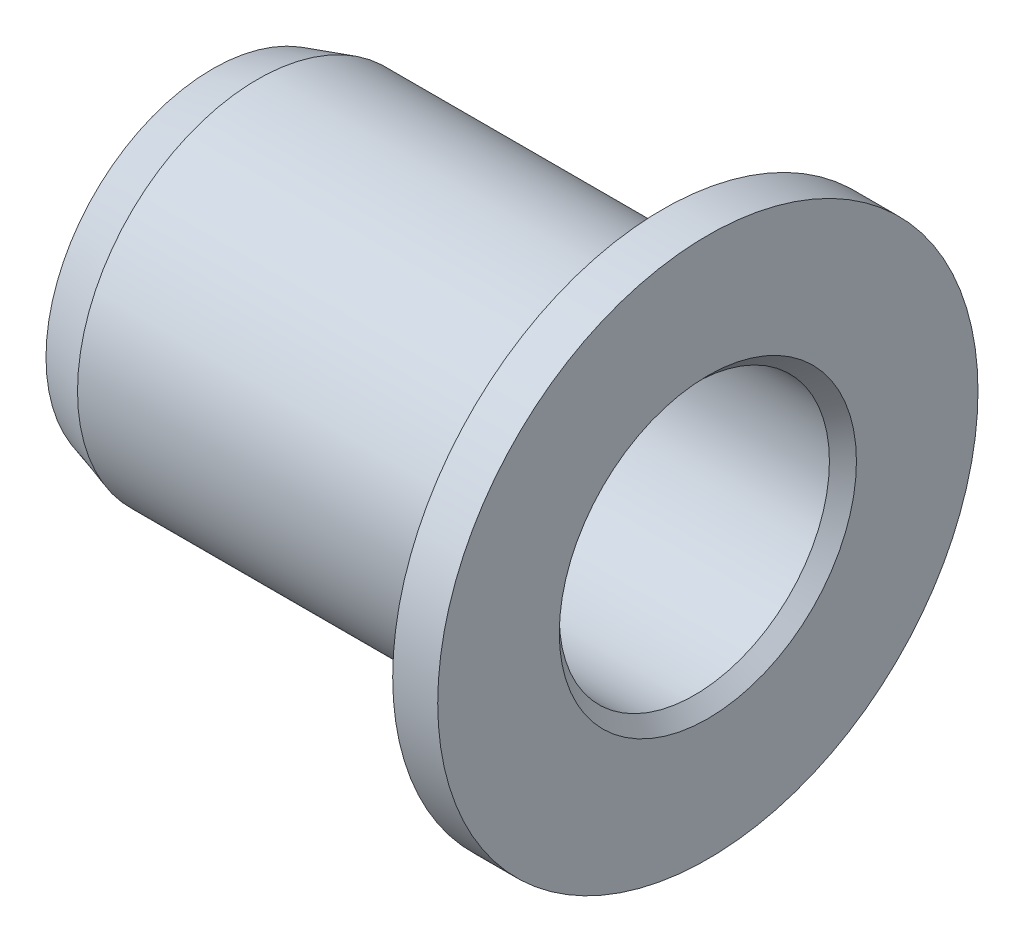
SolidWorks part; units mm, degrees
material "ﾎﾟﾘｵｷｼﾒﾁﾚﾝ(POM)ｱｾﾀｰﾙ共重合体"
ref_plane "正面" through (0, 0, 0) normal (0, 0, 1) x (1, 0, 0)
ref_plane "平面" through (0, 0, 0) normal (0, 1, 0) x (1, 0, 0)
ref_plane "右側面" through (0, 0, 0) normal (1, 0, 0) x (0, 0, -1)
sketch "ｽｹｯﾁ1" plane through (0, 0, 0) normal (0, 0, 1) x (1, 0, 0)
  line L0 (0, 0) -> (12541.7355, 0) construction
  line L1 (0, 3) -> (0, 6)
  line L2 (0, 6) -> (-1, 6)
  line L3 (-1, 6) -> (-1, 4)
  line L4 (-1, 4) -> (-11, 4)
  line L5 (-11, 4) -> (-11, 3)
  line L6 (-11, 3) -> (0, 3)
  dimension "D1" = 10
  dimension "D2" = 6
  dimension "D3" = 8
  dimension "D4" = 1
  dimension "D5" = 12
revolve "回転1" add sketch "ｽｹｯﾁ1" angle 360 about L0
chamfer "面取り1" distance 0.3 angle 45 1 edges at (0, 0, 3)
chamfer "面取り2" distance 1 distance2 0.3 1 edges at (-11, 0, 4)
